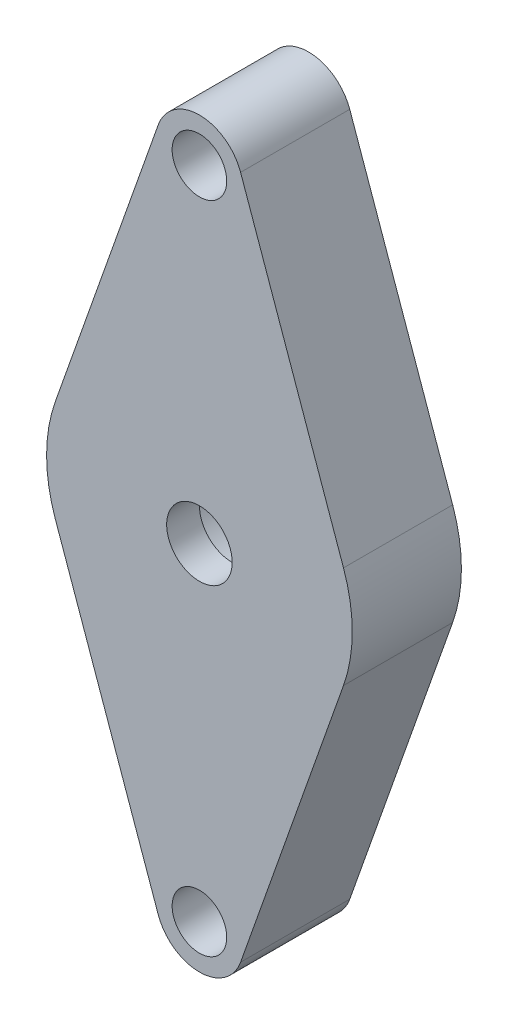
SolidWorks part; units mm, degrees
ref_plane "Front Plane" through (0, 0, 0) normal (0, 0, 1) x (1, 0, 0)
ref_plane "Top Plane" through (0, 0, 0) normal (0, 1, 0) x (1, 0, 0)
ref_plane "Right Plane" through (0, 0, 0) normal (1, 0, 0) x (0, 0, -1)
sketch "Sketch1" plane through (0, 0, 0) normal (0, 0, 1) x (1, 0, 0)
  line L0 (0, 0) -> (15.0079, 0) construction
  line L1 (-6.5997, -2.3333) -> (-1.8856, -15.6667)
  line L2 (1.8856, -15.6667) -> (6.5997, -2.3333)
  line L3 (-6.5997, 2.3333) -> (-1.8856, 15.6667)
  line L4 (1.8856, 15.6667) -> (6.5997, 2.3333)
  circle A0 centre (0, 0) radius 3
  arc A1 (-6.5997, 2.3333) -> (-6.5997, -2.3333) centre (0, 0) ccw
  arc A2 (1.8856, 15.6667) -> (-1.8856, 15.6667) centre (0, 15) ccw
  arc A3 (1.8856, -15.6667) -> (-1.8856, -15.6667) centre (0, -15) cw
  circle A4 centre (0, 15) radius 1.25
  circle A5 centre (0, -15) radius 1.25
  circle A6 centre (0, 0) radius 7 construction
  arc A7 (6.5997, -2.3333) -> (6.5997, 2.3333) centre (0, 0) ccw
  dimension "D1" = 6
  dimension "D3" = 4
  dimension "D5" = 2.5
  dimension "D6" = 2.5
  dimension "D4" = 15
  dimension "D2" = 4
extrude "Boss-Extrude1" add sketch "Sketch1" along normal blind 5
sketch "Sketch2" plane through (0, 0, 5) normal (0, 0, 1) x (1, 0, 0)
  circle A0 centre (0, 0) radius 3
  circle A1 centre (0, 0) radius 1.5
  dimension "D1" = 6
  dimension "D2" = 3
extrude "Boss-Extrude2" add sketch "Sketch2" against normal blind 1.5
